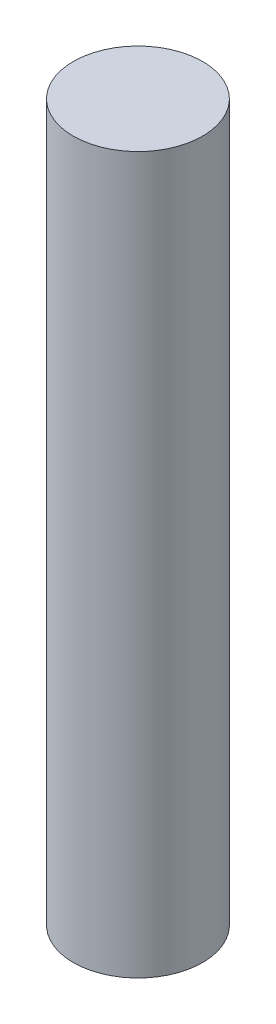
SolidWorks part; units mm, degrees
ref_plane "Front Plane" through (0, 0, 0) normal (0, 0, 1) x (1, 0, 0)
ref_plane "Top Plane" through (0, 0, 0) normal (0, 1, 0) x (1, 0, 0)
ref_plane "Right Plane" through (0, 0, 0) normal (1, 0, 0) x (0, 0, -1)
sketch "Sketch1" plane through (0, 0, 0) normal (0, 1, 0) x (1, 0, 0)
  line L0 (9.5439, 31.652) -> (9.5439, 170.9398) construction
  circle A0 centre (0, 0) radius 45
  point P6 (0, 62.6807)
  point P7 (4.9152, 33.5535)
  point P8 (9.5439, 31.652)
  point P9 (0, 0)
  dimension "D1" = 90
extrude "Boss-Extrude1" add sketch "Sketch1" along normal blind 223 and the other way blind 275 contours A0
